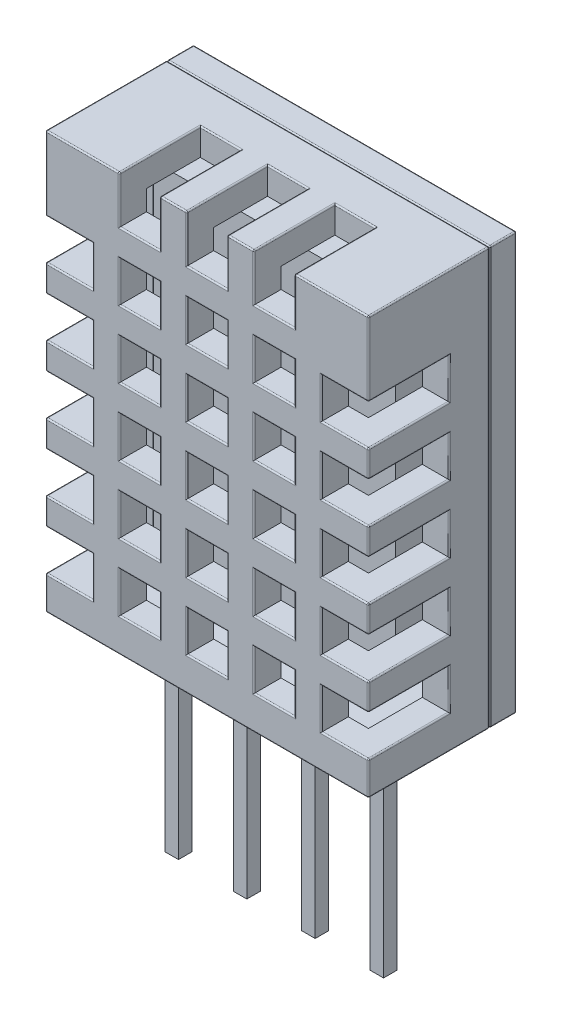
SolidWorks part; units mm, degrees
ref_plane "Front Plane" through (0, 0, 0) normal (0, 0, 1) x (1, 0, 0)
ref_plane "Top Plane" through (0, 0, 0) normal (0, 1, 0) x (1, 0, 0)
ref_plane "Right Plane" through (0, 0, 0) normal (1, 0, 0) x (0, 0, -1)
sketch "Sketch1" plane through (0, 0, 0) normal (0, 0, 1) x (1, 0, 0)
  line L1 (0, 0) -> (12, 0)
  line L2 (0, 0) -> (0, 15.5)
  line L3 (0, 15.5) -> (12, 15.5)
  line L4 (12, 0) -> (12, 15.5)
  dimension "D1" = 12
  dimension "D2" = 15.5
extrude "Boss-Extrude1" add sketch "Sketch1" along normal blind 5.5
sketch "Sketch2" plane through (0, 0, 0) normal (0, -1, 0) x (1, 0, 0)
  line L0 (0, 5.5) -> (0, 0) construction
  line L1 (1.94, 3) -> (2.44, 3)
  line L2 (1.94, 3) -> (1.94, 2.5)
  line L3 (1.94, 2.5) -> (2.44, 2.5)
  line L4 (2.44, 3) -> (2.44, 2.5)
  line L5 (0, 2.75) -> (12, 2.75) construction
  line L6 (12, 5.5) -> (12, 0) construction
  line L7 (4.48, 3) -> (4.98, 3)
  line L8 (4.48, 3) -> (4.48, 2.5)
  line L9 (4.48, 2.5) -> (4.98, 2.5)
  line L10 (4.98, 3) -> (4.98, 2.5)
  line L11 (7.02, 3) -> (7.52, 3)
  line L12 (7.02, 3) -> (7.02, 2.5)
  line L13 (7.02, 2.5) -> (7.52, 2.5)
  line L14 (7.52, 3) -> (7.52, 2.5)
  line L15 (9.56, 3) -> (10.06, 3)
  line L16 (9.56, 3) -> (9.56, 2.5)
  line L17 (9.56, 2.5) -> (10.06, 2.5)
  line L18 (10.06, 3) -> (10.06, 2.5)
  point P11 (1.94, 2.75)
  dimension "D1" = 0.5
  dimension "D2" = 0.5
  dimension "D3" = 1.94
  dimension "D4" = 4
extrude "Boss-Extrude2" add sketch "Sketch2" along normal blind 8
shell "Shell2" thickness 1
sketch "Sketch3" plane through (0, 0, 5.5) normal (0, 0, 1) x (1, 0, 0)
  line L0 (12, 15.5) -> (0, 15.5) construction
  line L1 (2.75, 15.5) -> (4.25, 15.5)
  line L2 (2.75, 15.5) -> (2.75, 13.75)
  line L3 (2.75, 13.75) -> (4.25, 13.75)
  line L4 (4.25, 15.5) -> (4.25, 13.75)
  line L5 (5.25, 15.5) -> (6.75, 15.5)
  line L6 (5.25, 15.5) -> (5.25, 13.75)
  line L7 (5.25, 13.75) -> (6.75, 13.75)
  line L8 (6.75, 15.5) -> (6.75, 13.75)
  line L9 (7.75, 15.5) -> (9.25, 15.5)
  line L10 (7.75, 15.5) -> (7.75, 13.75)
  line L11 (7.75, 13.75) -> (9.25, 13.75)
  line L12 (9.25, 15.5) -> (9.25, 13.75)
  line L13 (0, 15.5) -> (0, 0) construction
  dimension "D1" = 1.5
  dimension "D2" = 1.75
  dimension "D4" = 2.75
  dimension "D3" = 3
extrude "Cut-Extrude1" cut sketch "Sketch3" against normal blind 3
sketch "Sketch4" plane through (0, 0, 5.5) normal (0, 0, 1) x (1, 0, 0)
  line L0 (2.75, 13.75) -> (4.25, 13.75) construction
  line L1 (2.75, 12.75) -> (4.25, 12.75)
  line L2 (2.75, 12.75) -> (2.75, 11.25)
  line L3 (2.75, 11.25) -> (4.25, 11.25)
  line L4 (4.25, 12.75) -> (4.25, 11.25)
  line L5 (0, 15.5) -> (0, 0) construction
  line L6 (5.25, 12.75) -> (6.75, 12.75)
  line L7 (5.25, 12.75) -> (5.25, 11.25)
  line L8 (5.25, 11.25) -> (6.75, 11.25)
  line L9 (6.75, 12.75) -> (6.75, 11.25)
  line L10 (7.75, 12.75) -> (9.25, 12.75)
  line L11 (7.75, 12.75) -> (7.75, 11.25)
  line L12 (7.75, 11.25) -> (9.25, 11.25)
  line L13 (9.25, 12.75) -> (9.25, 11.25)
  line L14 (5.25, 10.25) -> (6.75, 10.25)
  line L15 (5.25, 10.25) -> (5.25, 8.75)
  line L16 (5.25, 8.75) -> (6.75, 8.75)
  line L17 (6.75, 10.25) -> (6.75, 8.75)
  line L18 (7.75, 10.25) -> (9.25, 10.25)
  line L19 (7.75, 10.25) -> (7.75, 8.75)
  line L20 (7.75, 8.75) -> (9.25, 8.75)
  line L21 (9.25, 10.25) -> (9.25, 8.75)
  line L22 (5.25, 7.75) -> (6.75, 7.75)
  line L23 (5.25, 7.75) -> (5.25, 6.25)
  line L24 (5.25, 6.25) -> (6.75, 6.25)
  line L25 (6.75, 7.75) -> (6.75, 6.25)
  line L26 (7.75, 7.75) -> (9.25, 7.75)
  line L27 (7.75, 7.75) -> (7.75, 6.25)
  line L28 (7.75, 6.25) -> (9.25, 6.25)
  line L29 (9.25, 7.75) -> (9.25, 6.25)
  line L30 (5.25, 5.25) -> (6.75, 5.25)
  line L31 (5.25, 5.25) -> (5.25, 3.75)
  line L32 (5.25, 3.75) -> (6.75, 3.75)
  line L33 (6.75, 5.25) -> (6.75, 3.75)
  line L34 (7.75, 5.25) -> (9.25, 5.25)
  line L35 (7.75, 5.25) -> (7.75, 3.75)
  line L36 (7.75, 3.75) -> (9.25, 3.75)
  line L37 (9.25, 5.25) -> (9.25, 3.75)
  line L38 (5.25, 2.75) -> (6.75, 2.75)
  line L39 (5.25, 2.75) -> (5.25, 1.25)
  line L40 (5.25, 1.25) -> (6.75, 1.25)
  line L41 (6.75, 2.75) -> (6.75, 1.25)
  line L42 (7.75, 2.75) -> (9.25, 2.75)
  line L43 (7.75, 2.75) -> (7.75, 1.25)
  line L44 (7.75, 1.25) -> (9.25, 1.25)
  line L45 (9.25, 2.75) -> (9.25, 1.25)
  line L46 (2.75, 10.25) -> (4.25, 10.25)
  line L47 (2.75, 10.25) -> (2.75, 8.75)
  line L48 (2.75, 8.75) -> (4.25, 8.75)
  line L49 (4.25, 10.25) -> (4.25, 8.75)
  line L50 (2.75, 7.75) -> (4.25, 7.75)
  line L51 (2.75, 7.75) -> (2.75, 6.25)
  line L52 (2.75, 6.25) -> (4.25, 6.25)
  line L53 (4.25, 7.75) -> (4.25, 6.25)
  line L54 (2.75, 5.25) -> (4.25, 5.25)
  line L55 (2.75, 5.25) -> (2.75, 3.75)
  line L56 (2.75, 3.75) -> (4.25, 3.75)
  line L57 (4.25, 5.25) -> (4.25, 3.75)
  line L58 (2.75, 2.75) -> (4.25, 2.75)
  line L59 (2.75, 2.75) -> (2.75, 1.25)
  line L60 (2.75, 1.25) -> (4.25, 1.25)
  line L61 (4.25, 2.75) -> (4.25, 1.25)
  dimension "D1" = 1.5
  dimension "D2" = 1
  dimension "D3" = 2.75
  dimension "D4" = 3
  dimension "D5" = 5
extrude "Cut-Extrude2" cut sketch "Sketch4" against normal blind 3
sketch "Sketch5" plane through (0, 0, 5.5) normal (0, 0, 1) x (1, 0, 0)
  line L0 (0, 15.5) -> (0, 0) construction
  line L1 (0, 12.75) -> (1.75, 12.75)
  line L2 (0, 12.75) -> (0, 11.25)
  line L3 (0, 11.25) -> (1.75, 11.25)
  line L4 (1.75, 12.75) -> (1.75, 11.25)
  line L7 (2.75, 12.75) -> (2.75, 11.25) construction
  line L8 (10.25, 12.75) -> (12, 12.75)
  line L9 (10.25, 12.75) -> (10.25, 11.25)
  line L10 (10.25, 11.25) -> (12, 11.25)
  line L11 (12, 12.75) -> (12, 11.25)
  line L12 (10.25, 10.25) -> (12, 10.25)
  line L13 (10.25, 10.25) -> (10.25, 8.75)
  line L14 (10.25, 8.75) -> (12, 8.75)
  line L15 (12, 10.25) -> (12, 8.75)
  line L16 (10.25, 7.75) -> (12, 7.75)
  line L17 (10.25, 7.75) -> (10.25, 6.25)
  line L18 (10.25, 6.25) -> (12, 6.25)
  line L19 (12, 7.75) -> (12, 6.25)
  line L20 (10.25, 5.25) -> (12, 5.25)
  line L21 (10.25, 5.25) -> (10.25, 3.75)
  line L22 (10.25, 3.75) -> (12, 3.75)
  line L23 (12, 5.25) -> (12, 3.75)
  line L24 (10.25, 2.75) -> (12, 2.75)
  line L25 (10.25, 2.75) -> (10.25, 1.25)
  line L26 (10.25, 1.25) -> (12, 1.25)
  line L27 (12, 2.75) -> (12, 1.25)
  line L28 (0, 10.25) -> (1.75, 10.25)
  line L29 (0, 10.25) -> (0, 8.75)
  line L30 (0, 8.75) -> (1.75, 8.75)
  line L31 (1.75, 10.25) -> (1.75, 8.75)
  line L32 (0, 7.75) -> (1.75, 7.75)
  line L33 (0, 7.75) -> (0, 6.25)
  line L34 (0, 6.25) -> (1.75, 6.25)
  line L35 (1.75, 7.75) -> (1.75, 6.25)
  line L36 (0, 5.25) -> (1.75, 5.25)
  line L37 (0, 5.25) -> (0, 3.75)
  line L38 (0, 3.75) -> (1.75, 3.75)
  line L39 (1.75, 5.25) -> (1.75, 3.75)
  line L40 (0, 2.75) -> (1.75, 2.75)
  line L41 (0, 2.75) -> (0, 1.25)
  line L42 (0, 1.25) -> (1.75, 1.25)
  line L43 (1.75, 2.75) -> (1.75, 1.25)
  dimension "D1" = 1
  dimension "D2" = 2
  dimension "D3" = 5
extrude "Cut-Extrude3" cut sketch "Sketch5" against normal blind 3
sketch "Sketch6" plane through (0, 0, 0) normal (0, 0, -1) x (-1, 0, 0)
  line L4 (0, 0) -> (0, 15.5)
  line L5 (0, 15.5) -> (-12, 15.5)
  line L6 (-12, 15.5) -> (-12, 0)
  line L7 (-12, 0) -> (0, 0)
  line L8 (0, 0) -> (0, 15.5)
  line L9 (0, 15.5) -> (-12, 15.5)
  line L10 (-12, 15.5) -> (-12, 0)
  line L11 (-12, 0) -> (0, 0)
  line L12 (-1, 14.5) -> (-11, 14.5)
  line L13 (-1, 1) -> (-1, 14.5)
  line L14 (-11, 1) -> (-1, 1)
  line L15 (-11, 14.5) -> (-11, 1)
  line L16 (-1, 14.5) -> (-11, 14.5)
  line L17 (-1, 1) -> (-1, 14.5)
  line L18 (-11, 1) -> (-1, 1)
  line L19 (-11, 14.5) -> (-11, 1)
  dimension "D1" = 0
  dimension "D2" = 0
extrude "Cut-Extrude4" cut sketch "Sketch6" against normal blind 1
ref_plane "Plane1" through (0, 0, 0.99) normal (0, 0, 1) x (1, 0, 0)
sketch "Sketch8" plane through (0, 0, 0.99) normal (0, 0, 1) x (1, 0, 0)
  line L4 (0, 0) -> (12, 0)
  line L5 (0, 15.5) -> (0, 0)
  line L6 (12, 15.5) -> (0, 15.5)
  line L7 (12, 0) -> (12, 15.5)
  line L8 (0, 0) -> (12, 0)
  line L9 (0, 15.5) -> (0, 0)
  line L10 (12, 15.5) -> (0, 15.5)
  line L11 (12, 0) -> (12, 15.5)
  dimension "D1" = 0
extrude "Boss-Extrude3" add sketch "Sketch8" against normal blind 0.99 separate body
sketch "Sketch9" plane through (0, 0, 0) normal (0, -1, 0) x (1, 0, 0)
  line L0 (1.94, 3) -> (1.94, 2.5) construction
  line L1 (1.94, 2.5) -> (2.44, 2.5) construction
  line L2 (2.44, 2.5) -> (2.44, 3) construction
  line L3 (2.44, 3) -> (1.94, 3) construction
  line L4 (4.48, 3) -> (4.48, 2.5) construction
  line L5 (4.48, 2.5) -> (4.98, 2.5) construction
  line L6 (4.98, 2.5) -> (4.98, 3) construction
  line L7 (4.98, 3) -> (4.48, 3) construction
  line L8 (7.02, 3) -> (7.02, 2.5) construction
  line L9 (7.02, 2.5) -> (7.52, 2.5) construction
  line L10 (7.52, 2.5) -> (7.52, 3) construction
  line L11 (7.52, 3) -> (7.02, 3) construction
  line L12 (9.56, 3) -> (9.56, 2.5) construction
  line L13 (9.56, 2.5) -> (10.06, 2.5) construction
  line L14 (10.06, 2.5) -> (10.06, 3) construction
  line L15 (10.06, 3) -> (9.56, 3) construction
  line L16 (1.94, 3) -> (1.94, 2.5)
  line L17 (1.94, 2.5) -> (2.44, 2.5)
  line L18 (2.44, 2.5) -> (2.44, 3)
  line L19 (2.44, 3) -> (1.94, 3)
  line L20 (4.48, 3) -> (4.48, 2.5)
  line L21 (4.48, 2.5) -> (4.98, 2.5)
  line L22 (4.98, 2.5) -> (4.98, 3)
  line L23 (4.98, 3) -> (4.48, 3)
  line L24 (7.02, 3) -> (7.02, 2.5)
  line L25 (7.02, 2.5) -> (7.52, 2.5)
  line L26 (7.52, 2.5) -> (7.52, 3)
  line L27 (7.52, 3) -> (7.02, 3)
  line L28 (9.56, 3) -> (9.56, 2.5)
  line L29 (9.56, 2.5) -> (10.06, 2.5)
  line L30 (10.06, 2.5) -> (10.06, 3)
  line L31 (10.06, 3) -> (9.56, 3)
  line L32 (1.84, 3.1) -> (1.84, 2.4)
  line L33 (1.84, 2.4) -> (2.54, 2.4)
  line L34 (2.54, 2.4) -> (2.54, 3.1)
  line L35 (2.54, 3.1) -> (1.84, 3.1)
  line L36 (4.38, 3.1) -> (4.38, 2.4)
  line L37 (4.38, 2.4) -> (5.08, 2.4)
  line L38 (5.08, 2.4) -> (5.08, 3.1)
  line L39 (5.08, 3.1) -> (4.38, 3.1)
  line L40 (6.92, 3.1) -> (6.92, 2.4)
  line L41 (6.92, 2.4) -> (7.62, 2.4)
  line L42 (7.62, 2.4) -> (7.62, 3.1)
  line L43 (7.62, 3.1) -> (6.92, 3.1)
  line L44 (9.46, 3.1) -> (9.46, 2.4)
  line L45 (9.46, 2.4) -> (10.16, 2.4)
  line L46 (10.16, 2.4) -> (10.16, 3.1)
  line L47 (10.16, 3.1) -> (9.46, 3.1)
  dimension "D1" = 0.1
extrude "Cut-Extrude5" cut sketch "Sketch9" against normal blind 1
fillet "Fillet1" radius 0.05 106 edges at (2.19, 0, 2.4) (2.19, 0, 3.1) (4.73, 0, 2.4) (5.08, 0, 2.75) (4.73, 0, 3.1) (4.38, 0, 2.75) (7.62, 0, 2.75) (6.92, 0, 2.75) (9.81, 0, 2.4) (9.81, 0, 3.1) (9.46, 0, 2.75) (0, 12, 2.5) (0, 10.25, 4) (0, 9.5, 2.5) (0, 8.75, 4) (0, 7.75, 4) (0, 6.25, 4) (0, 5.25, 4) (0, 4.5, 2.5) (0, 3.75, 4) (0, 2, 2.5) (0, 1.25, 4) (0, 0, 3.25) (0, 7.75, 1) (9.25, 15.5, 4) (7.75, 15.5, 4) (6.75, 15.5, 4) (6, 15.5, 2.5) (4.25, 15.5, 4) (2.75, 15.5, 4) (0, 15.5, 3.25) (12, 0, 3.25) (12, 1.25, 4) (12, 2, 2.5) (12, 4.5, 2.5) (12, 5.25, 4) (12, 7, 2.5) (12, 11.25, 4) (12, 12, 2.5) (12, 12.75, 4) (12, 15.5, 3.25) (12, 7.75, 1) (0.875, 3.75, 5.5) (0.875, 5.25, 5.5) (0.875, 6.25, 5.5) (1.75, 7, 5.5) (0, 8.25, 5.5) (1.75, 9.5, 5.5) (3.5, 13.75, 5.5) (4.25, 14.625, 5.5) (4.75, 15.5, 5.5) (5.25, 14.625, 5.5) (7.25, 15.5, 5.5) (7.75, 14.625, 5.5) (9.25, 14.625, 5.5) (11.125, 11.25, 5.5) (12, 10.75, 5.5) (11.125, 8.75, 5.5) (12, 5.75, 5.5) (10.25, 4.5, 5.5) (11.125, 3.75, 5.5) (12, 3.25, 5.5) (11.125, 2.75, 5.5) (10.25, 2, 5.5) (11.125, 1.25, 5.5) (6, 0, 5.5) (0, 0.625, 5.5) (0.875, 1.25, 5.5) (1.75, 2, 5.5) (0.875, 2.75, 5.5) (0, 3.25, 5.5) (4.25, 12, 5.5) (3.5, 12.75, 5.5) (2.75, 12, 5.5) (5.25, 12, 5.5) (8.5, 11.25, 5.5) (6.75, 9.5, 5.5) (6, 10.25, 5.5) (5.25, 9.5, 5.5) (6, 8.75, 5.5) (8.5, 10.25, 5.5) (7.75, 9.5, 5.5) (8.5, 8.75, 5.5) (6.75, 7, 5.5) (6, 6.25, 5.5) (9.25, 7, 5.5) (8.5, 7.75, 5.5) (7.75, 7, 5.5) (8.5, 6.25, 5.5) (6.75, 4.5, 5.5) (6, 3.75, 5.5) (9.25, 4.5, 5.5) (8.5, 5.25, 5.5) (6, 2.75, 5.5) (5.25, 2, 5.5) (6, 1.25, 5.5) (9.25, 2, 5.5) (8.5, 2.75, 5.5) (3.5, 10.25, 5.5) (2.75, 9.5, 5.5) (3.5, 8.75, 5.5) (2.75, 7, 5.5) (3.5, 6.25, 5.5) (4.25, 4.5, 5.5) (3.5, 5.25, 5.5) (3.5, 1.25, 5.5)
fillet "Fillet2" radius 0.05 12 edges at (6, 15.5, 0.99) (0, 15.5, 0.495) (0, 7.75, 0.99) (0, 0, 0.495) (6, 0, 0.99) (12, 15.5, 0.495) (12, 0, 0.495) (12, 7.75, 0.99) (6, 15.5, 0) (0, 7.75, 0) (6, 0, 0) (12, 7.75, 0)
sketch "Sketch10" plane through (0, 0, 0.99) normal (0, 0, 1) x (1, 0, 0)
  line L14 (1.5, 1.5) -> (10.5, 1.5)
  line L15 (10.5, 1.5) -> (10.5, 14)
  line L16 (10.5, 14) -> (1.5, 14)
  line L17 (1.5, 14) -> (1.5, 1.5)
  line L18 (1.5, 1.5) -> (10.5, 1.5)
  line L19 (10.5, 1.5) -> (10.5, 14)
  line L20 (10.5, 14) -> (1.5, 14)
  line L21 (1.5, 14) -> (1.5, 1.5)
  dimension "D1" = 0.5
extrude "Boss-Extrude4" add sketch "Sketch10" along normal blind 2
